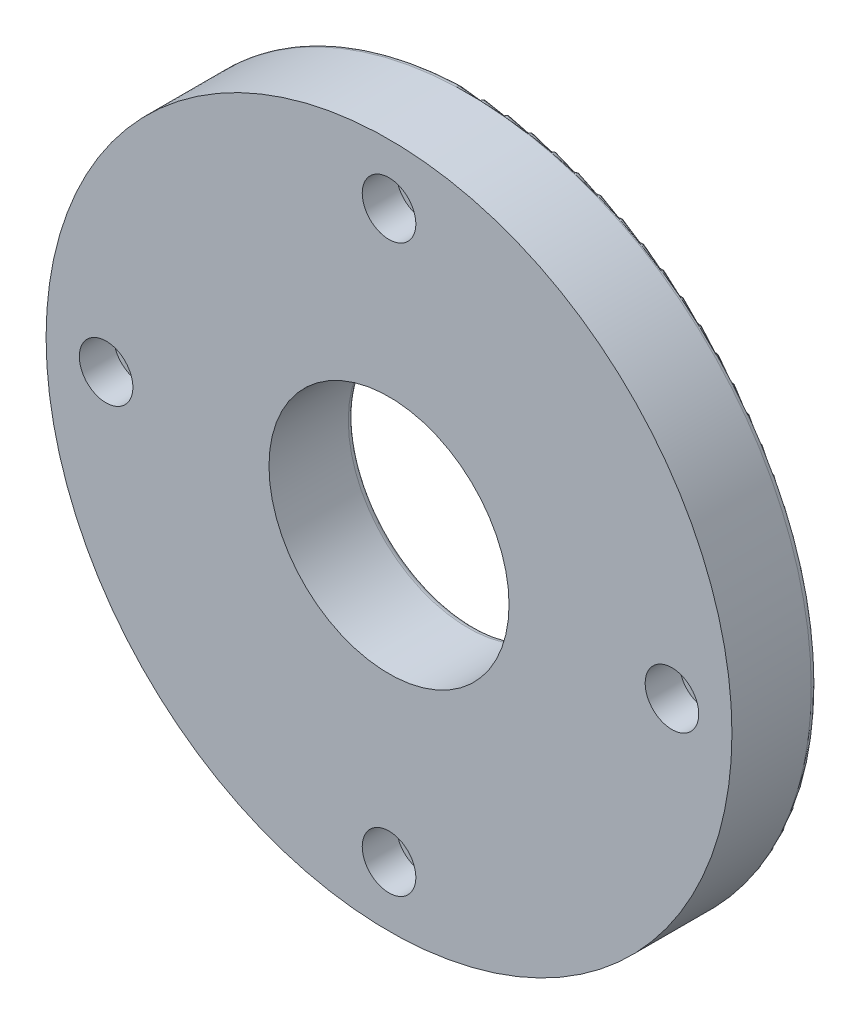
SolidWorks part; units mm, degrees
material "ABS PC"
ref_plane "Front Plane" through (0, 0, 0) normal (0, 0, 1) x (1, 0, 0)
ref_plane "Top Plane" through (0, 0, 0) normal (0, 1, 0) x (1, 0, 0)
ref_plane "Right Plane" through (0, 0, 0) normal (1, 0, 0) x (0, 0, -1)
sketch "Sketch1" plane through (0, 0, 0) normal (0, 0, 1) x (1, 0, 0)
  circle A0 centre (0, 0) radius 40
  circle A1 centre (0, 0) radius 14
  dimension "D1" = 80
  dimension "D2" = 28
extrude "Boss-Extrude1" add sketch "Sketch1" along normal blind 10
sketch "Sketch2" plane through (0, 0, 0) normal (0, 0, -1) x (-1, 0, 0)
  circle A0 centre (0, 33) radius 1.7
  circle A1 centre (33, 0) radius 1.7
  circle A2 centre (0, -33) radius 1.7
  circle A3 centre (-33, 0) radius 1.7
  point P12 (0, 0)
  dimension "D2" = 3.4
  dimension "D1" = 33
  dimension "D3" = 4
extrude "Cut-Extrude3" cut sketch "Sketch2" against normal blind 10
sketch "Sketch4" plane through (0, 0, 0) normal (0, 0, -1) x (-1, 0, 0)
  circle A0 centre (0, 33) radius 3.125
  circle A1 centre (33, 0) radius 3.125
  circle A2 centre (0, -33) radius 3.125
  circle A3 centre (-33, 0) radius 3.125
  point P12 (0, 0)
  dimension "D1" = 6.25
  dimension "D2" = 4
extrude "Cut-Extrude4" cut sketch "Sketch4" along normal blind 4 from offset 10 offset against normal yes
fillet "Fillet1" radius 0.75 6 edges at (14, 0, 0) (40, 0, 0) (31.3, 0, 0) (-1.7, -33, 0) (-34.7, 0, 0) (-1.7, 33, 0)
